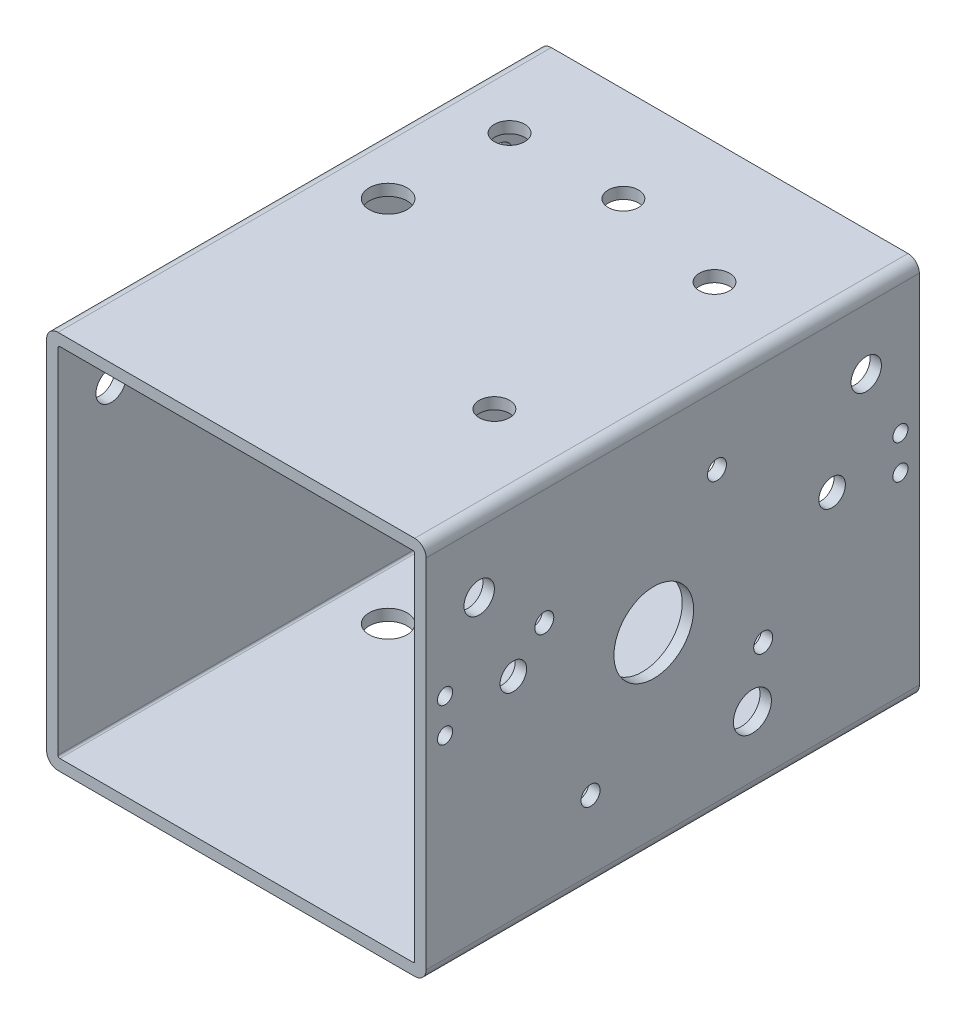
SolidWorks part; units mm, degrees
ref_plane "Front Plane" through (0, 0, 0) normal (0, 0, 1) x (1, 0, 0)
ref_plane "Top Plane" through (0, 0, 0) normal (0, 1, 0) x (1, 0, 0)
ref_plane "Right Plane" through (0, 0, 0) normal (1, 0, 0) x (0, 0, -1)
sketch "Sketch1" plane through (0, 0, 0) normal (0, 0, 1) x (1, 0, 0)
  line L1 (-50, 50) -> (50, 50)
  line L2 (-50, 50) -> (-50, -50)
  line L3 (-50, -50) -> (50, -50)
  line L4 (50, 50) -> (50, -50)
  line L5 (-50, 50) -> (50, -50) construction
  line L6 (-50, -50) -> (50, 50) construction
  point P0 (0, 0)
  dimension "D1" = 100
  dimension "D2" = 100
extrude "Extrude-Thin1" add sketch "Sketch1" along normal blind 130 thin
fillet "Fillet1" radius 0.5 4 edges at (-47, -47, 65) (-47, 47, 65) (47, 47, 65) (47, -47, 65)
fillet "Fillet2" radius 3 4 edges at (50, -50, 65) (-50, -50, 65) (50, 50, 65) (-50, 50, 65)
sketch "Holes - top" plane through (0, 0, 0) normal (0, 1, 0) x (1, 0, 0)
  line L0 (-3, 0) -> (-3, -130) construction
  line L1 (47, -130) -> (-47, -130) construction
  line L2 (-23, 0) -> (-23, -130) construction
  line L3 (47, 0) -> (-47, 0) construction
  line L4 (17, 0) -> (17, -130) construction
  circle A0 centre (-34, -56) radius 11 construction
  circle A1 centre (28, -90) radius 11 construction
  circle A2 centre (28, -32) radius 11 construction
  dimension "D4" = 22
  dimension "D1" = 40
  dimension "D2" = 40
  dimension "D3" = 32
  dimension "D5" = 56
  dimension "D6" = 3
hole_wizard "Ø8.0 (8) Diameter Hole2" positions "Sketch6" profile "Sketch5" hole size "Ø8.0" standard "ANSI Metric" end condition through all
sketch "Sketch6" plane through (0, 50, 0) normal (0, 1, 0) x (1, 0, 0)
  point P0 (28, -32)
  point P6 (28, -90)
sketch "Sketch5" plane through (28, 50, 32) normal (1, 0, 0) x (0, 0, 1)
  line L0 (0, 0) -> (0, 100)
  line L1 (0, 100) -> (4, 100)
  line L2 (4, 100) -> (4, 0)
  line L5 (4, 0) -> (0, 0)
  line L11 (0, -6.35) -> (0, 107.95) construction
  dimension "Thru Hole Dia." = 8
  dimension "Thru Hole Depth" = 100
sketch "Holes - side" plane through (0, 0, 0) normal (1, 0, 0) x (0, 0, -1)
  line L0 (0, 0) -> (-130, 0) construction
  line L1 (-130, -47) -> (-130, 47) construction
  line L2 (-130, 20) -> (0, 20) construction
  line L3 (0, -47) -> (0, 47) construction
  line L4 (-130, -20) -> (0, -20) construction
  circle A0 centre (-116, 31) radius 11 construction
  circle A1 centre (-14, 31) radius 11 construction
  circle A2 centre (-44, -31) radius 11 construction
  dimension "D1" = 40
  dimension "D2" = 22
  dimension "D3" = 14
  dimension "D4" = 14
  dimension "D5" = 44
hole_wizard "Ø8.0 (8) Diameter Hole3" positions "Sketch9" profile "Sketch8" hole size "Ø8.0" standard "ANSI Metric" end condition through all
sketch "Sketch9" plane through (50, 0, 0) normal (1, 0, 0) x (0, 0, -1)
  point P0 (-14, 31)
  point P3 (-116, 31)
sketch "Sketch8" plane through (50, 31, 14) normal (0, 1, 0) x (0, 0, -1)
  line L0 (0, 0) -> (0, 100)
  line L1 (0, 100) -> (4, 100)
  line L2 (4, 100) -> (4, 0)
  line L5 (4, 0) -> (0, 0)
  line L11 (0, -6.35) -> (0, 107.95) construction
  dimension "Thru Hole Dia." = 8
  dimension "Thru Hole Depth" = 100
hole_wizard "Ø10.0 (10) Diameter Hole1" positions "Sketch12" profile "Sketch11" hole size "Ø10.0" standard "ANSI Metric" end condition through all
sketch "Sketch12" plane through (0, 50, 0) normal (0, 1, 0) x (1, 0, 0)
  point P0 (-34, -56)
sketch "Sketch11" plane through (-34, 50, 56) normal (1, 0, 0) x (0, 0, 1)
  line L0 (0, 0) -> (0, 100)
  line L1 (0, 100) -> (5, 100)
  line L2 (5, 100) -> (5, 0)
  line L5 (5, 0) -> (0, 0)
  line L11 (0, -6.35) -> (0, 107.95) construction
  dimension "Thru Hole Dia." = 10
  dimension "Thru Hole Depth" = 100
hole_wizard "Ø10.0 (10) Diameter Hole2" positions "Sketch14" profile "Sketch13" hole size "Ø10.0" standard "ANSI Metric" end condition through all
sketch "Sketch14" plane through (50, 0, 0) normal (1, 0, 0) x (0, 0, -1)
  point P0 (-44, -31)
sketch "Sketch13" plane through (50, -31, 44) normal (0, 1, 0) x (0, 0, -1)
  line L0 (0, 0) -> (0, 100)
  line L1 (0, 100) -> (5, 100)
  line L2 (5, 100) -> (5, 0)
  line L5 (5, 0) -> (0, 0)
  line L11 (0, -6.35) -> (0, 107.95) construction
  dimension "Thru Hole Dia." = 10
  dimension "Thru Hole Depth" = 100
hole_wizard "M8x1.25 Tapped Hole1" positions "Sketch18" profile "Sketch17" tap size "M8x1.25" standard "ANSI Metric"
sketch "Sketch18" plane through (-50, 0, 0) normal (-1, 0, 0) x (0, 0, 1)
  line L0 (56, 35) -> (56, -15) construction
  point P0 (56, -15)
  point P2 (56, 35)
  dimension "D1" = 56
  dimension "D2" = 35
  dimension "D3" = 15
sketch "Sketch17" plane through (-50, -15, 56) normal (0, 1, 0) x (0, 0, 1)
  line L0 (0, 0) -> (0, 3)
  line L1 (0, 3) -> (3.4, 3)
  line L2 (3.4, 3) -> (3.4, 0)
  line L5 (3.4, 0) -> (0, 0)
  line L11 (0, -6.35) -> (0, 107.95) construction
  dimension "Thru Tap Drill Dia." = 6.8
  dimension "Thru Tap Drill Depth" = 3
cosmetic thread "Hole Thread1" parameters "D2"=8
cosmetic thread "Hole Thread2" parameters "D2"=8
hole_wizard "M8x1.25 Tapped Hole2" positions "Sketch21" profile "Sketch20" tap size "M8x1.25" standard "ANSI Metric"
sketch "Sketch21" plane through (0, -50, 0) normal (0, -1, 0) x (-1, 0, 0)
  line L0 (20, -44) -> (-35, -44) construction
  point P0 (20, -44)
  point P2 (-35, -44)
  dimension "D1" = 44
  dimension "D2" = 35
  dimension "D3" = 20
sketch "Sketch20" plane through (-20, -50, 44) normal (1, 0, 0) x (0, 0, -1)
  line L0 (0, 0) -> (0, 3)
  line L1 (0, 3) -> (3.4, 3)
  line L2 (3.4, 3) -> (3.4, 0)
  line L5 (3.4, 0) -> (0, 0)
  line L11 (0, -6.35) -> (0, 107.95) construction
  dimension "Thru Tap Drill Dia." = 6.8
  dimension "Thru Tap Drill Depth" = 3
cosmetic thread "Hole Thread3" parameters "D2"=8
cosmetic thread "Hole Thread4" parameters "D2"=8
sketch "Holes - Nema 23 motor" plane through (0, 0, 0) normal (1, 0, 0) x (0, 0, -1)
  line L0 (-98.8427, 16.6524) -> (-53.3476, 28.8427) construction
  line L1 (-98.8427, 16.6524) -> (-86.6524, -28.8427) construction
  line L2 (-53.3476, 28.8427) -> (-41.1573, -16.6524) construction
  line L3 (-86.6524, -28.8427) -> (-41.1573, -16.6524) construction
  line L4 (-98.8427, 16.6524) -> (-41.1573, -16.6524) construction
  line L5 (-53.3476, 28.8427) -> (-86.6524, -28.8427) construction
  line L6 (0, 0) -> (-130, 0) construction
  point P1 (-70, 0)
  dimension "D1" = 70
  dimension "D2" = 47.1
  dimension "D3" = 47.1
  dimension "D4" = 15
hole_wizard "Ø21.0 (21) Diameter Hole1" positions "Sketch24" profile "Sketch23" hole size "Ø21.0" standard "ANSI Metric"
sketch "Sketch24" plane through (50, 0, 0) normal (1, 0, 0) x (0, 0, -1)
  point P0 (-70, 0)
sketch "Sketch23" plane through (50, 0, 70) normal (0, 1, 0) x (0, 0, -1)
  line L0 (0, 0) -> (0, 3)
  line L1 (0, 3) -> (10.5, 3)
  line L2 (10.5, 3) -> (10.5, 0)
  line L5 (10.5, 0) -> (0, 0)
  line L11 (0, -6.35) -> (0, 107.95) construction
  dimension "Thru Hole Dia." = 21
  dimension "Thru Hole Depth" = 3
hole_wizard "Ø5.0 (5) Diameter Hole1" positions "Sketch26" profile "Sketch25" hole size "Ø5.0" standard "ANSI Metric"
sketch "Sketch26" plane through (50, 0, 0) normal (1, 0, 0) x (0, 0, -1)
  point P0 (-41.1573, -16.6524)
  point P3 (-53.3476, 28.8427)
  point P6 (-98.8427, 16.6524)
  point P9 (-86.6524, -28.8427)
sketch "Sketch25" plane through (50, -16.6524, 41.1573) normal (0, 1, 0) x (0, 0, -1)
  line L0 (0, 0) -> (0, 3)
  line L1 (0, 3) -> (2.5, 3)
  line L2 (2.5, 3) -> (2.5, 0)
  line L5 (2.5, 0) -> (0, 0)
  line L11 (0, -6.35) -> (0, 107.95) construction
  dimension "Thru Hole Dia." = 5
  dimension "Thru Hole Depth" = 3
hole_wizard "Ø8.0 (8) Diameter Hole4" positions "Sketch29" profile "Sketch28" hole size "Ø8.0" standard "ANSI Metric"
sketch "Sketch29" plane through (0, 50, 0) normal (0, 1, 0) x (1, 0, 0)
  line L0 (-3, 0) -> (-3, -130) construction
  point P0 (-3, -25)
  dimension "D2" = 7
sketch "Sketch28" plane through (-3, 50, 25) normal (1, 0, 0) x (0, 0, 1)
  line L0 (0, 0) -> (0, 3)
  line L1 (0, 3) -> (4, 3)
  line L2 (4, 3) -> (4, 0)
  line L5 (4, 0) -> (0, 0)
  line L11 (0, -6.35) -> (0, 107.95) construction
  dimension "Thru Hole Dia." = 8
  dimension "Thru Hole Depth" = 3
sketch "Sketch31" plane through (50, 0, 0) normal (1, 0, 0) x (0, 0, -1)
  line L0 (0, -47) -> (0, 47) construction
  line L1 (-130, 50) -> (0, 50) construction
  line L2 (-65, 117.0212) -> (-65, -118.5233) construction
  line L3 (-130, -47) -> (-130, 47) construction
  circle A0 centre (-5, 4) radius 2
  circle A1 centre (-5, 13) radius 2
  circle A2 centre (-125, 13) radius 2
  circle A3 centre (-125, 4) radius 2
  circle A4 centre (-23, 8.5) radius 3.5
  circle A5 centre (-107, 8.5) radius 3.5
  dimension "D1" = 4
  dimension "D2" = 4
  dimension "D3" = 9
  dimension "D4" = 5
  dimension "D5" = 46
  dimension "D6" = 5
  dimension "D8" = 7
  dimension "D9" = 18
  dimension "D7" = 65
  dimension "D10" = 4.5
extrude "Cut-Extrude1" cut sketch "Sketch31" against normal up to next
hole_wizard "Ø8.0 (8) Diameter Hole5" positions "Sketch32" profile "Sketch33" hole size "Ø8.0" standard "ANSI Metric"
sketch "Sketch32" plane through (0, 50, 0) normal (0, 1, 0) x (1, 0, 0)
  line L1 (47, 0) -> (-47, 0) construction
  circle A0 centre (-3, -25) radius 4 construction
  point P0 (-33, -25)
  dimension "D1" = 30
  dimension "D2" = 25
sketch "Sketch33" plane through (-33, 50, 25) normal (1, 0, 0) x (0, 0, 1)
  line L0 (0, 0) -> (0, 3)
  line L1 (0, 3) -> (4, 3)
  line L2 (4, 3) -> (4, 0)
  line L5 (4, 0) -> (0, 0)
  line L11 (0, -6.35) -> (0, 107.95) construction
  dimension "Thru Hole Dia." = 8
  dimension "Thru Hole Depth" = 3
equation "\"L\"= 130"
equation "\"D1@Extrude-Thin1\"=\"L\""
equation "\"d-bearing\"= 22'diameter of bearing"
equation "\"D4@Holes - top\"=\"d-bearing\""
equation "\"D2@Holes - side\"=\"d-bearing\""
